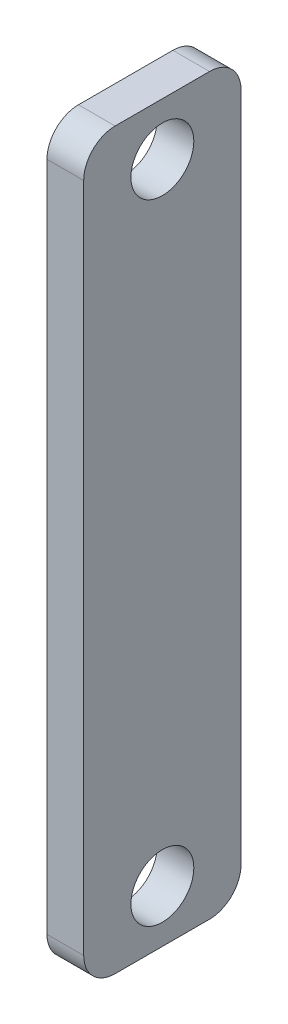
SolidWorks part; units mm, degrees
ref_plane "Front Plane" through (0, 0, 0) normal (0, 0, 1) x (1, 0, 0)
ref_plane "Top Plane" through (0, 0, 0) normal (0, 1, 0) x (1, 0, 0)
ref_plane "Right Plane" through (0, 0, 0) normal (1, 0, 0) x (0, 0, -1)
sketch "Sketch3" plane through (0, 0, 0) normal (1, 0, 0) x (0, 0, -1)
  line L1 (3, 0) -> (12, 0)
  line L2 (0, -3) -> (0, -67)
  line L3 (3, -70) -> (12, -70)
  line L4 (15, -3) -> (15, -67)
  circle A0 centre (7.5, -5) radius 3
  circle A1 centre (7.5, -65) radius 3
  arc A2 (0, -67) -> (3, -70) centre (3, -67) ccw
  arc A3 (12, -70) -> (15, -67) centre (12, -67) ccw
  arc A4 (12, 0) -> (15, -3) centre (12, -3) cw
  arc A5 (3, 0) -> (0, -3) centre (3, -3) ccw
  point P11 (0, -70)
  point P14 (15, -70)
  point P17 (15, 0)
  point P20 (0, 0)
  dimension "D3" = 6
  dimension "D4" = 6
  dimension "D7" = 3
  dimension "D1" = 70
  dimension "D2" = 15
  dimension "D5" = 5
  dimension "D6" = 5
extrude "Boss-Extrude2" add sketch "Sketch3" along normal mid plane 3.5
